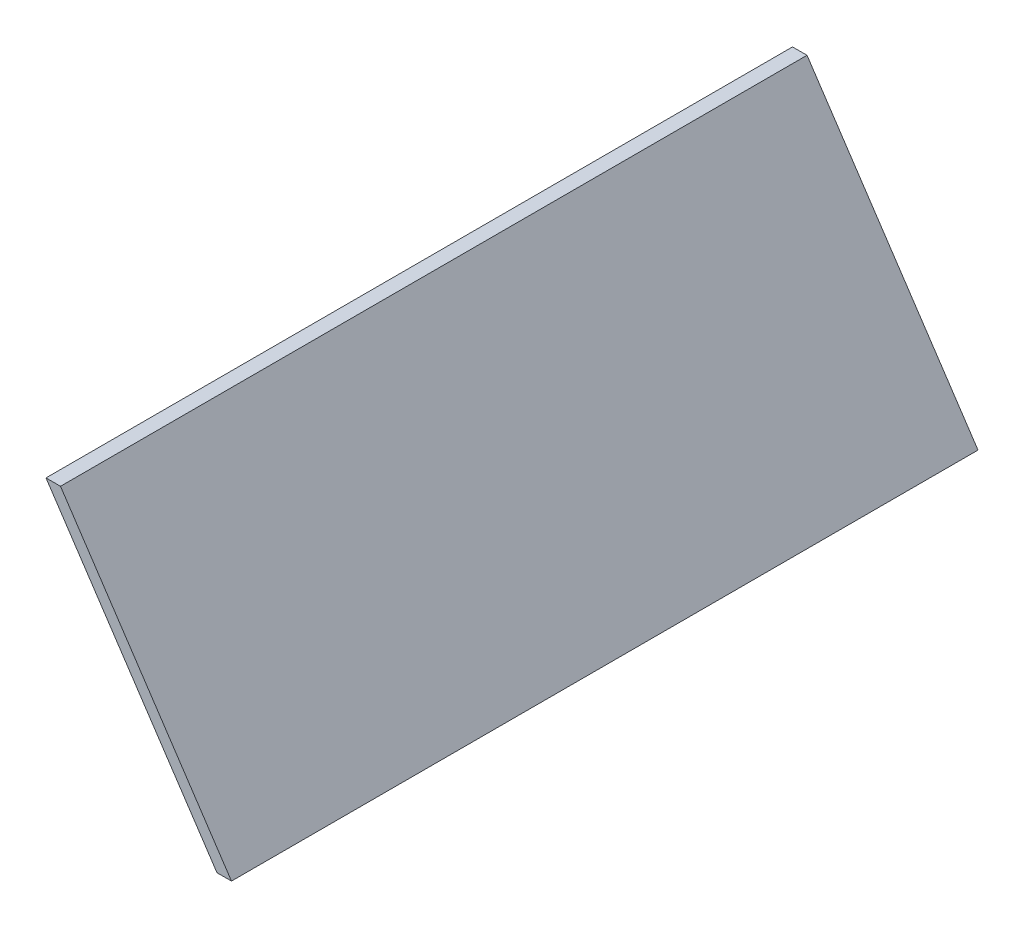
SolidWorks part; units mm, degrees
material "5052-H34"
ref_plane "Front Plane" through (0, 0, 0) normal (0, 0, 1) x (1, 0, 0)
ref_plane "Top Plane" through (0, 0, 0) normal (0, 1, 0) x (1, 0, 0)
ref_plane "Right Plane" through (0, 0, 0) normal (1, 0, 0) x (0, 0, -1)
sketch "Sketch1" plane through (0, 0, 0) normal (0, 0, 1) x (1, 0, 0)
  line L6 (-194.8923, -15.5826) -> (-148.0708, -85.8151)
  line L7 (-148.0708, -85.8151) -> (-142.6803, -85.8151)
  line L9 (-190.2721, -14.4272) -> (-142.6803, -85.8151)
  line L10 (-142.6803, -85.8151) -> (-125.3132, -85.8151)
  line L11 (-199.8594, 9.5074) -> (-217.2492, 9.5074) construction
  line L12 (-194.8923, -15.5826) -> (-211.619, 9.5074)
  line L14 (-190.2721, -14.4272) -> (-206.2285, 9.5074)
  line L15 (-211.619, 9.5074) -> (-206.2285, 9.5074)
  point P0 (-199.8594, 9.5074)
  dimension "D1" = 123.69
  dimension "D2" = 123.69
  dimension "D3" = 180
  dimension "D4" = 25.09
  dimension "D5" = 70.2325
  dimension "D6" = 5.3905
  dimension "D7" = 180
extrude "Boss-Extrude1" add sketch "Sketch1" along normal blind 277.48 contours L9 L14 L15 L12 L6 L7
